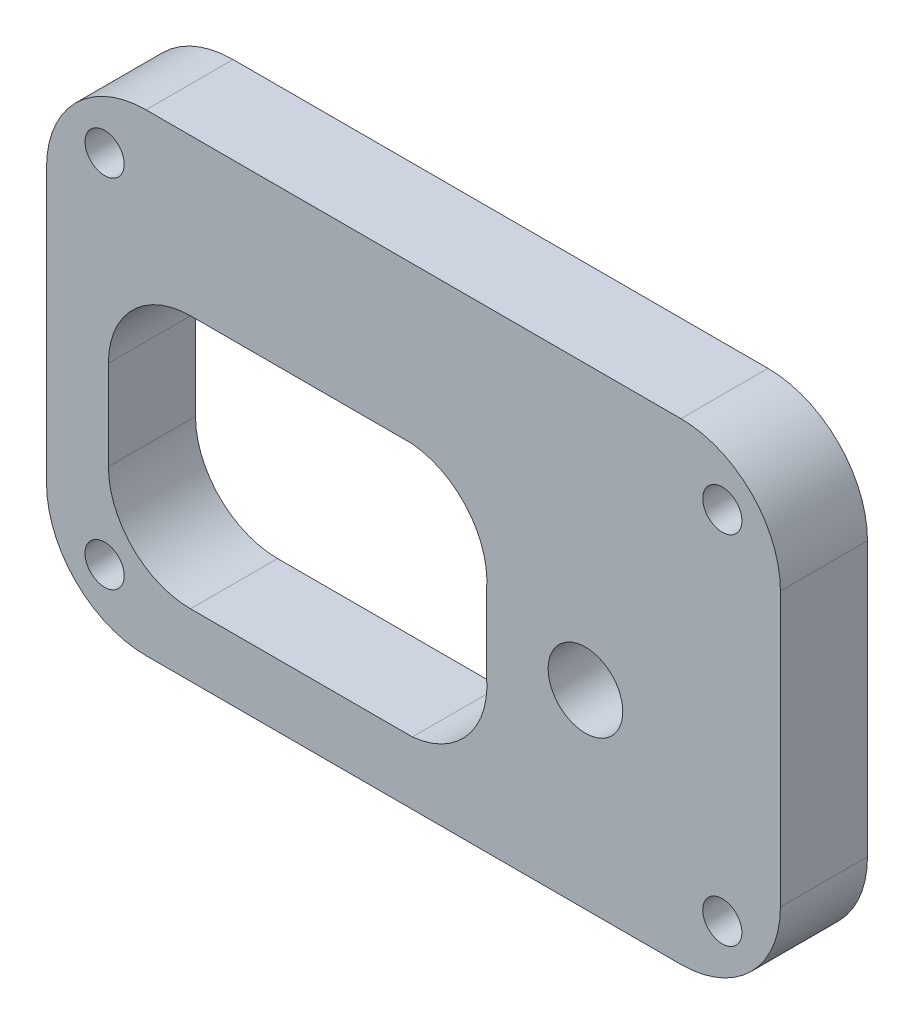
SolidWorks part; units mm, degrees
ref_plane "Front Plane" through (0, 0, 0) normal (0, 0, 1) x (1, 0, 0)
ref_plane "Top Plane" through (0, 0, 0) normal (0, 1, 0) x (1, 0, 0)
ref_plane "Right Plane" through (0, 0, 0) normal (1, 0, 0) x (0, 0, -1)
sketch "Sketch1" plane through (0, 0, 0) normal (0, 0, 1) x (1, 0, 0)
  line L1 (0, 0) -> (37.465, 0)
  line L2 (0, 0) -> (0, 24.13)
  line L3 (0, 24.13) -> (37.465, 24.13)
  line L4 (37.465, 0) -> (37.465, 24.13)
  dimension "D1" = 24.13
  dimension "D2" = 37.465
extrude "Boss-Extrude1" add sketch "Sketch1" along normal blind 4.445
sketch "Sketch2" plane through (0, 0, 4.445) normal (0, 0, 1) x (1, 0, 0)
  line L0 (37.465, 12.065) -> (35.5918, 12.065)
  line L1 (18.7325, 24.13) -> (18.7325, 22.9235)
  line L2 (0, 12.065) -> (1.8733, 12.065)
  line L3 (18.7325, 0) -> (18.7325, 1.2065)
  line L4 (3.175, 7.493) -> (3.175, 16.637)
  line L5 (7.493, 20.955) -> (29.972, 20.955)
  line L6 (34.29, 16.637) -> (34.29, 7.493)
  line L7 (29.972, 3.175) -> (7.493, 3.175)
  line L8 (0, 24.13) -> (0, 0) construction
  line L9 (37.465, 24.13) -> (0, 24.13) construction
  line L10 (0, 24.13) -> (0, 0)
  line L11 (37.465, 24.13) -> (0, 24.13)
  line L12 (7.1548, 20.955) -> (29.6338, 20.955)
  line L13 (34.29, 16.637) -> (34.29, 7.493)
  line L14 (29.972, 3.175) -> (7.493, 3.175)
  line L15 (3.175, 7.493) -> (3.175, 16.637)
  line L16 (18.9016, 24.13) -> (18.9016, 22.9235) construction
  line L17 (0, 12.065) -> (1.8733, 12.065) construction
  line L18 (37.465, 5.08) -> (37.465, 19.05)
  line L19 (33.0615, 24.13) -> (4.7418, 24.13)
  line L20 (0, 19.05) -> (0, 5.08)
  line L21 (5.2491, 0) -> (32.5541, 0.0113)
  line L22 (6.4453, 1.2065) -> (31.0198, 1.2065)
  line L23 (35.5918, 5.7785) -> (35.5918, 18.3515)
  line L24 (30.6815, 22.9235) -> (6.107, 22.9235)
  line L25 (1.8733, 18.3515) -> (1.8733, 5.7785)
  line L26 (37.465, 0) -> (37.465, 24.13) construction
  line L27 (18.9016, 1.2065) -> (18.9016, 0.0056) construction
  line L28 (35.5918, 12.065) -> (37.465, 12.065) construction
  arc A0 (29.972, 20.955) -> (34.29, 16.637) centre (29.972, 16.637) cw
  arc A1 (34.29, 7.493) -> (29.972, 3.175) centre (29.972, 7.493) cw
  arc A2 (7.493, 3.175) -> (3.175, 7.493) centre (7.493, 7.493) cw
  arc A3 (3.175, 16.637) -> (7.493, 20.955) centre (7.493, 16.637) cw
  arc A4 (34.29, 16.637) -> (29.6338, 20.955) centre (29.972, 16.6503) ccw
  arc A5 (29.972, 3.175) -> (34.29, 7.493) centre (29.972, 7.493) ccw
  arc A6 (3.175, 7.493) -> (7.493, 3.175) centre (7.493, 7.493) ccw
  arc A7 (7.1548, 20.955) -> (3.175, 16.637) centre (7.493, 16.6503) ccw
  arc A8 (37.465, 19.05) -> (33.0615, 24.13) centre (32.3852, 19.0952) ccw
  arc A9 (4.7418, 24.13) -> (0, 19.05) centre (5.08, 19.0613) ccw
  arc A10 (0, 5.08) -> (5.2491, 0) centre (5.08, 5.0772) ccw
  arc A11 (32.5541, 0.0113) -> (37.465, 5.08) centre (32.385, 5.0885) ccw
  arc A12 (6.107, 22.9235) -> (1.8733, 18.3515) centre (6.4452, 18.364) ccw
  arc A13 (1.8733, 5.7785) -> (6.4453, 1.2065) centre (6.4453, 5.7785) ccw
  arc A14 (35.5918, 18.3515) -> (30.6815, 22.9235) centre (31.0198, 18.364) ccw
  arc A15 (31.0198, 1.2065) -> (35.5918, 5.7785) centre (31.0198, 5.7785) ccw
  point P11 (3.175, 12.065)
  dimension "D3" = 4.318
  dimension "D12" = 5.08
  dimension "D13" = 5.08
  dimension "D14" = 5.08
  dimension "D15" = 5.08
  dimension "D4" = 17.78
  dimension "D5" = 31.115
  dimension "D10" = 1.2065
  dimension "D11" = 1.8732
  dimension "D16" = 13.97
  dimension "D17" = 13.97
  dimension "D18" = 27.305
extrude "Cut-Extrude2" cut sketch "Sketch2" against normal blind 2.54 contours L22 A15 L23 A14 L24 A12 L25 A13 A7 L12 L5 A4 L6 A1 L7 A2 L4 | A3 L4 A2 L7 A1 L6 A0 L5 | L12 A7 A3 | A0 A4 L5
fillet "Fillet1" radius 5.08 4 edges at (37.465, 24.13, 2.2225) (37.465, 0, 2.2225) (0, 0, 2.2225) (0, 24.13, 2.2225)
sketch "Sketch3" plane through (0, 0, 1.905) normal (0, 0, 1) x (1, 0, 0)
  line L0 (20.3901, 8.5258) -> (20.8175, 10.8382)
  line L1 (16.1777, 15.4192) -> (9.8512, 15.4014)
  line L2 (5.1247, 10.9098) -> (5.4787, 8.4542)
  line L3 (10.296, 4.0601) -> (15.7329, 3.9625)
  line L4 (7.3509, 16.159) -> (18.678, 16.159)
  line L5 (22.4639, 11.5628) -> (22.4639, 7.8011)
  line L6 (7.3509, 3.205) -> (18.678, 3.205)
  line L7 (3.1599, 11.968) -> (3.1599, 7.396)
  line L8 (13.0144, 16.159) -> (13.0144, 3.205) construction
  line L9 (3.1599, 9.682) -> (22.4639, 9.682) construction
  line L10 (5.3017, 9.682) -> (20.6038, 9.682) construction
  line L11 (13.0144, 15.4103) -> (13.0144, 4.0113) construction
  arc A0 (18.678, 16.159) -> (22.4639, 11.5628) centre (18.2729, 11.968) cw
  arc A1 (18.678, 3.205) -> (22.4639, 7.8011) centre (18.2729, 7.396) ccw
  arc A2 (3.1599, 7.396) -> (7.3509, 3.205) centre (7.3509, 7.396) ccw
  arc A3 (7.3509, 16.159) -> (3.1599, 11.968) centre (7.3509, 11.968) ccw
  spline S0 degree 2 poles (20.8175, 10.8382) (20.82, 10.9908) (20.8004, 11.3402) (20.7305, 11.8546) (20.4376, 12.8472) (19.5293, 14.1968) (18.1669, 15.0756) (17.1627, 15.3498) (16.6574, 15.409) (16.3028, 15.4216) (16.1777, 15.4192) knots 0 0 0 0.046875 0.09375 0.1875 0.375 0.625 0.8125 0.90625 0.953125 1 1 1
  spline S1 degree 2 poles (9.8512, 15.4014) (9.7263, 15.4062) (9.3701, 15.4003) (8.8583, 15.3498) (7.8502, 15.0933) (6.4708, 14.2372) (5.5408, 12.9075) (5.2293, 11.9156) (5.1513, 11.4096) (5.1252, 11.0626) (5.1247, 10.9098) knots 0 0 0 0.046875 0.09375 0.1875 0.375 0.625 0.8125 0.90625 0.953125 1 1 1
  spline S2 degree 2 poles (5.4787, 8.4542) (5.4823, 8.3016) (5.5157, 7.9533) (5.6058, 7.442) (5.9378, 6.4617) (6.8987, 5.1491) (8.2948, 4.3249) (9.309, 4.0905) (9.8163, 4.0514) (10.1711, 4.0528) (10.296, 4.0601) knots 0 0 0 0.046875 0.09375 0.1875 0.375 0.625 0.8125 0.90625 0.953125 1 1 1
  spline S3 degree 2 poles (15.7329, 3.9625) (15.8578, 3.9596) (16.2138, 3.9709) (16.7248, 4.0292) (17.7289, 4.301) (19.095, 5.1782) (20.0047, 6.5219) (20.301, 7.5185) (20.3712, 8.0256) (20.392, 8.373) (20.3901, 8.5258) knots 0 0 0 0.046875 0.09375 0.1875 0.375 0.625 0.8125 0.90625 0.953125 1 1 1
extrude "Cut-Extrude4" cut sketch "Sketch3" against normal blind 2.54 contours L4 A0 L5 A1 L6 A2 L7 A3
sketch "Sketch4" plane through (0, 0, 1.905) normal (0, 0, 1) x (1, 0, 0)
  line L0 (22.4639, 9.682) -> (34.8414, 9.682) construction
  line L1 (23.3842, 17.5759) -> (23.3842, 1.8039)
  line L2 (22.4639, 11.5628) -> (22.4639, 7.8011) construction
  line L3 (31.6392, 1.8039) -> (23.3842, 1.8039)
  line L4 (23.3842, 17.5759) -> (31.6392, 17.5759)
  line L5 (31.6392, 17.5759) -> (31.6392, 1.8039)
  line L6 (27.5117, 17.5759) -> (27.5117, 1.8039) construction
  circle A0 centre (27.5117, 9.6899) radius 1.27
  point P5 (29.5303, 7.3913)
extrude "Cut-Extrude5" cut sketch "Sketch4" against normal blind 2.54 contours A0
sketch "Sketch5" plane through (0, 0, 1.905) normal (0, 0, 1) x (1, 0, 0)
  circle A0 centre (27.5117, 9.6899) radius 1.27 construction
  circle A1 centre (27.5117, 9.6899) radius 1.27
  circle A2 centre (27.5117, 9.6899) radius 1.905
  dimension "D1" = 3.81
extrude "Cut-Extrude6" cut sketch "Sketch5" against normal blind 0.635
sketch "Sketch6" plane through (0, 0, 4.445) normal (0, 0, 1) x (1, 0, 0)
  line L0 (1.8733, 12.065) -> (35.5918, 12.065) construction
  line L1 (18.3943, 22.9235) -> (18.3943, 1.2065) construction
  line L2 (1.5428, 18.4772) -> (1.5428, 5.6528)
  line L3 (6.2063, 0.9893) -> (31.2723, 0.9893)
  line L4 (6.4453, 1.2065) -> (31.0198, 1.2065)
  line L5 (35.5918, 5.7785) -> (35.5918, 18.3515)
  line L6 (30.6815, 22.9235) -> (6.107, 22.9235)
  line L7 (1.8732, 18.3515) -> (1.8733, 5.7785)
  line L8 (6.4453, 1.2065) -> (31.0198, 1.2065)
  line L9 (35.5918, 5.7785) -> (35.5918, 18.3515)
  line L10 (30.6815, 22.9235) -> (6.107, 22.9235)
  line L11 (1.8732, 18.3515) -> (1.8733, 5.7785)
  line L12 (35.9357, 5.6528) -> (35.9357, 18.4772)
  line L13 (30.9273, 23.1407) -> (5.8613, 23.1407)
  arc A0 (31.2723, 0.9893) -> (35.9357, 5.6528) centre (31.2723, 5.6528) ccw
  arc A1 (35.9357, 18.4772) -> (30.9273, 23.1407) centre (31.2723, 18.49) ccw
  arc A2 (1.5428, 5.6528) -> (6.2063, 0.9893) centre (6.2063, 5.6528) ccw
  arc A3 (5.8613, 23.1407) -> (1.5428, 18.4772) centre (6.2063, 18.49) ccw
  arc A4 (31.0198, 1.2065) -> (35.5918, 5.7785) centre (31.0198, 5.7785) ccw
  arc A5 (35.5918, 18.3515) -> (30.6815, 22.9235) centre (31.0198, 18.364) ccw
  arc A6 (6.107, 22.9235) -> (1.8732, 18.3515) centre (6.4452, 18.364) ccw
  arc A7 (1.8733, 5.7785) -> (6.4453, 1.2065) centre (6.4453, 5.7785) ccw
  arc A8 (31.0198, 1.2065) -> (35.5918, 5.7785) centre (31.0198, 5.7785) ccw
  arc A9 (35.5918, 18.3515) -> (30.6815, 22.9235) centre (31.0198, 18.364) ccw
  arc A10 (6.107, 22.9235) -> (1.8732, 18.3515) centre (6.4452, 18.364) ccw
  arc A11 (1.8733, 5.7785) -> (6.4453, 1.2065) centre (6.4453, 5.7785) ccw
  dimension "D1" = 0
extrude "Cut-Extrude7" cut sketch "Sketch6" against normal up to surface (2.54 mm away) up to face at (29.4167, 9.6899, 1.905)
sketch "Sketch7" plane through (0, 0, 1.905) normal (0, 0, 1) x (1, 0, 0)
  line L4 (7.3509, 16.159) -> (18.678, 16.159) construction
  line L5 (7.3509, 16.159) -> (18.678, 16.159)
  line L6 (3.1599, 11.968) -> (3.1599, 7.396) construction
  line L8 (6.2063, 0.9893) -> (31.2723, 0.9893)
  line L9 (35.9357, 5.6528) -> (35.9357, 18.4772)
  line L10 (30.9273, 23.1407) -> (5.8613, 23.1407)
  line L11 (1.5428, 18.4772) -> (1.5428, 5.6528)
  line L12 (6.2063, 0.9893) -> (31.2723, 0.9893)
  line L13 (35.9357, 5.6528) -> (35.9357, 18.4772)
  line L14 (30.9273, 23.1407) -> (5.8613, 23.1407)
  line L15 (1.5428, 18.4772) -> (1.5428, 5.6528)
  line L16 (3.1599, 11.968) -> (3.1599, 7.396)
  line L17 (7.3509, 3.205) -> (18.678, 3.205) construction
  line L18 (7.3509, 3.205) -> (18.678, 3.205)
  line L19 (22.4639, 11.5628) -> (22.4639, 7.8011) construction
  line L20 (22.4639, 11.5628) -> (22.4639, 7.8011)
  circle A4 centre (27.5117, 9.6899) radius 1.27 construction
  circle A5 centre (27.5117, 9.6899) radius 1.27
  circle A6 centre (27.5117, 9.6899) radius 1.905 construction
  circle A7 centre (27.5117, 9.6899) radius 1.905
  arc A8 (1.5428, 5.6528) -> (6.2063, 0.9893) centre (6.2063, 5.6528) ccw
  arc A9 (31.2723, 0.9893) -> (35.9357, 5.6528) centre (31.2723, 5.6528) ccw
  arc A10 (35.9357, 18.4772) -> (30.9273, 23.1407) centre (31.2723, 18.49) ccw
  arc A11 (5.8613, 23.1407) -> (1.5428, 18.4772) centre (6.2063, 18.49) ccw
  arc A12 (1.5428, 5.6528) -> (6.2063, 0.9893) centre (6.2063, 5.6528) ccw
  arc A13 (31.2723, 0.9893) -> (35.9357, 5.6528) centre (31.2723, 5.6528) ccw
  arc A14 (35.9357, 18.4772) -> (30.9273, 23.1407) centre (31.2723, 18.49) ccw
  arc A15 (5.8613, 23.1407) -> (1.5428, 18.4772) centre (6.2063, 18.49) ccw
  arc A16 (7.3509, 16.159) -> (3.1599, 11.968) centre (7.3509, 11.968) ccw construction
  arc A17 (7.3509, 16.159) -> (3.1599, 11.968) centre (7.3509, 11.968) ccw
  arc A19 (3.1599, 7.396) -> (7.3509, 3.205) centre (7.3509, 7.396) ccw construction
  arc A20 (3.1599, 7.396) -> (7.3509, 3.205) centre (7.3509, 7.396) ccw
  arc A21 (22.4639, 11.5628) -> (18.678, 16.159) centre (18.2729, 11.968) ccw construction
  arc A22 (22.4639, 11.5628) -> (18.678, 16.159) centre (18.2729, 11.968) ccw
  arc A23 (18.678, 3.205) -> (22.4639, 7.8011) centre (18.2729, 7.396) ccw construction
  arc A24 (18.678, 3.205) -> (22.4639, 7.8011) centre (18.2729, 7.396) ccw
  circle M9 centre (27.5117, 9.6899) radius 1.905
  arc M10 (3.1599, 11.968) -> (7.3509, 16.159) centre (7.3509, 11.968) cw
  line M11 (7.3509, 16.159) -> (18.678, 16.159)
  arc M12 (18.678, 16.159) -> (22.4639, 11.5628) centre (18.2729, 11.968) cw
  line M13 (22.4639, 11.5628) -> (22.4639, 7.8011)
  arc M14 (22.4639, 7.8011) -> (18.678, 3.205) centre (18.2729, 7.396) cw
  line M15 (18.678, 3.205) -> (7.3509, 3.205)
  arc M16 (7.3509, 3.205) -> (3.1599, 7.396) centre (7.3509, 7.396) cw
  line M17 (3.1599, 7.396) -> (3.1599, 11.968)
  arc M18 (1.5428, 5.6528) -> (6.2063, 0.9893) centre (6.2063, 5.6528) ccw
  line M19 (6.2063, 0.9893) -> (31.2723, 0.9893)
  arc M20 (31.2723, 0.9893) -> (35.9357, 5.6528) centre (31.2723, 5.6528) ccw
  line M21 (35.9357, 5.6528) -> (35.9357, 18.4772)
  arc M22 (35.9357, 18.4772) -> (30.9273, 23.1407) centre (31.2723, 18.49) ccw
  line M23 (30.9273, 23.1407) -> (5.8613, 23.1407)
  arc M24 (5.8613, 23.1407) -> (1.5428, 18.4772) centre (6.2063, 18.49) ccw
  line M25 (1.5428, 18.4772) -> (1.5428, 5.6528)
  dimension "D1" = 0
extrude "Boss-Extrude2" add sketch "Sketch7" along normal up to surface (2.54 mm away) contours M25 M18 M19 M20 M21 M22 M23 M24 M17 M10 M11 M12 M13 M14 M15 M16 M9 up to face at (18.6657, 12.0665, 4.445)
sketch "Sketch8" plane through (0, 0, 0) normal (0, 0, -1) x (-1, 0, 0)
  line L0 (-35.9771, 22.6421) -> (-34.4992, 21.1642)
  line L1 (-37.465, 12.065) -> (0, 12.065) construction
  line L2 (-37.465, 5.08) -> (-37.465, 19.05) construction
  line L3 (0, 19.05) -> (0, 5.08) construction
  line L4 (-18.7325, 24.13) -> (-18.7325, 0) construction
  line L5 (-32.385, 24.13) -> (-5.08, 24.13) construction
  line L6 (-5.08, 0) -> (-32.385, 0) construction
  arc A0 (-32.385, 24.13) -> (-37.465, 19.05) centre (-32.385, 19.05) ccw construction
  circle A1 centre (-34.4992, 21.1642) radius 1
  circle A2 centre (-34.4992, 2.9658) radius 1
  circle A3 centre (-2.9658, 2.9658) radius 1
  circle A4 centre (-2.9658, 21.1642) radius 1
  dimension "D2" = 2
  dimension "D1" = 2.09
extrude "Cut-Extrude8" cut sketch "Sketch8" against normal through all
